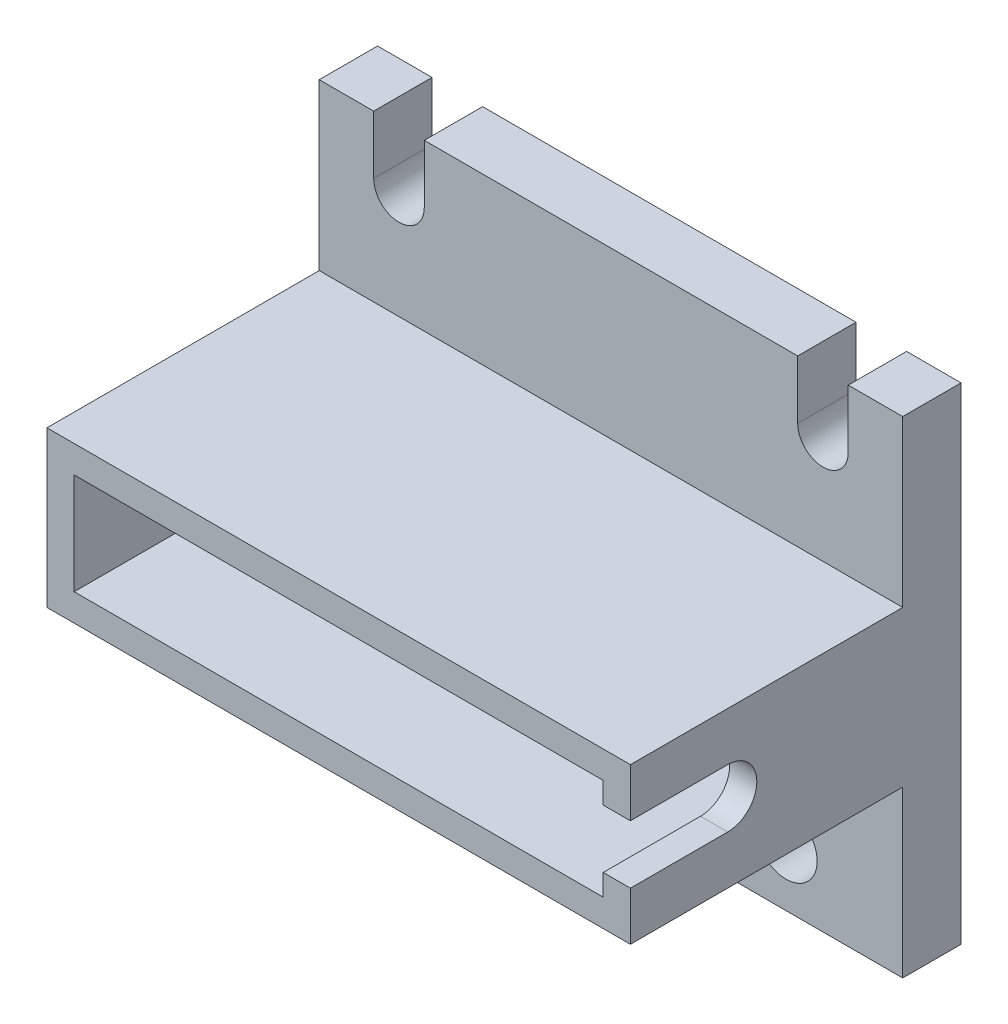
SolidWorks part; units mm, degrees
ref_plane "Спереди" through (0, 0, 0) normal (0, 0, 1) x (1, 0, 0)
ref_plane "Сверху" through (0, 0, 0) normal (0, 1, 0) x (1, 0, 0)
ref_plane "Справа" through (0, 0, 0) normal (1, 0, 0) x (0, 0, -1)
sketch "Эскиз1" plane through (0, 0, 0) normal (0, 0, 1) x (1, 0, 0)
  line L1 (-75, -62.5) -> (75, -62.5)
  line L2 (-75, -62.5) -> (-75, 62.5)
  line L3 (-75, 62.5) -> (75, 62.5)
  line L4 (75, -62.5) -> (75, 62.5)
  line L5 (-75, -62.5) -> (75, 62.5) construction
  line L6 (-75, 62.5) -> (75, -62.5) construction
  point P0 (0, 0)
  dimension "D1" = 125
  dimension "D2" = 150
extrude "Бобышка-Вытянуть1" add sketch "Эскиз1" along normal blind 15
sketch "Эскиз2" plane through (0, 0, 15) normal (0, 0, 1) x (1, 0, 0)
  line L0 (75, -62.5) -> (75, 62.5) construction
  line L1 (-75, -20) -> (75, -20)
  line L2 (-75, -20) -> (-75, 20)
  line L3 (-75, 20) -> (75, 20)
  line L4 (75, -20) -> (75, 20)
  line L5 (-75, -20) -> (75, 20) construction
  line L6 (-75, 20) -> (75, -20) construction
  point P0 (0, 0)
  dimension "D1" = 40
extrude "Бобышка-Вытянуть2" add sketch "Эскиз2" along normal blind 70
sketch "Эскиз3" plane through (0, 0, 85) normal (0, 0, 1) x (1, 0, 0)
  line L0 (68, 13) -> (-68, 13)
  line L1 (-68, 13) -> (-68, -13)
  line L2 (-68, -13) -> (68, -13)
  line L3 (68, -13) -> (68, 13)
  line L4 (75, -20) -> (75, 20)
  line L5 (75, 20) -> (-75, 20)
  line L6 (-75, 20) -> (-75, -20)
  line L7 (-75, -20) -> (75, -20)
  line L8 (75, -20) -> (75, 20)
  line L9 (75, 20) -> (-75, 20)
  line L10 (-75, 20) -> (-75, -20)
  line L11 (-75, -20) -> (75, -20)
  dimension "D1" = 0
  dimension "D2" = 7
extrude "Вырез-Вытянуть1" cut sketch "Эскиз3" against normal through all contours L2 L3 L0 L1
sketch "Эскиз4" plane through (0, 0, 15) normal (0, 0, 1) x (1, 0, 0)
  line L0 (75, -62.5) -> (75, -20) construction
  line L1 (-75, -62.5) -> (75, -62.5) construction
  line L2 (48, 47.5) -> (48, 62.5)
  line L3 (75, 62.5) -> (-75, 62.5) construction
  line L4 (48, 62.5) -> (61, 62.5)
  line L5 (61, 62.5) -> (61, 47.5)
  line L6 (75, 20) -> (75, 62.5) construction
  circle A0 centre (45, -47.5) radius 8
  circle A1 centre (54.5, 47.5) radius 6.5
  dimension "D1" = 30
  dimension "D2" = 15
  dimension "D3" = 16
  dimension "D5" = 13
  dimension "D4" = 15
  dimension "D6" = 14
extrude "Вырез-Вытянуть2" cut sketch "Эскиз4" against normal through all contours A0 | A1 L5 L4 L2 | A1 L4
sketch "Эскиз5" plane through (0, 0, 0) normal (1, 0, 0) x (0, 0, -1)
  line L0 (-85, -20) -> (-15, -62.5)
rib "Ребро1" sketch "Эскиз5" sketch "Эскиз5" thickness 20 extrusion direction parallel to sketch draft on no parameters "D1"=20
mirror "Зеркальное отражение1" about plane through (0, 0, 0) normal (1, 0, 0) of "Вырез-Вытянуть2"
sketch "Sketch1" plane through (75, 0, 0) normal (1, 0, 0) x (0, 0, -1)
  line L0 (-85, 0) -> (-60, 0) construction
  line L1 (-85, -20) -> (-85, 20) construction
  line L2 (-85, 7.5) -> (-60, 7.5)
  line L3 (-85, -7.5) -> (-60, -7.5)
  arc A0 (-85, 7.5) -> (-85, -7.5) centre (-85, 0) ccw
  arc A1 (-60, -7.5) -> (-60, 7.5) centre (-60, 0) ccw
  point P5 (-72.5, 0)
  dimension "D1" = 15
  dimension "D2" = 25
extrude "Cut-Extrude1" cut sketch "Sketch1" against normal up to next
